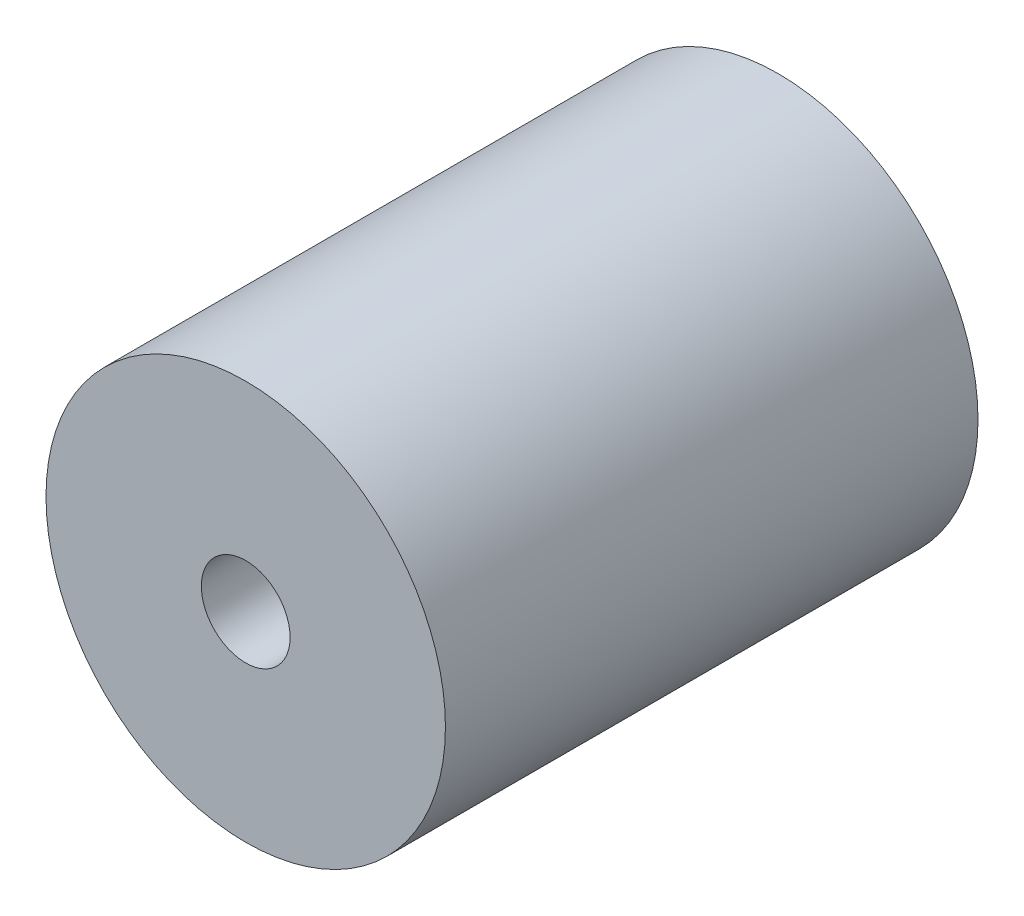
SolidWorks part; units mm, degrees
ref_plane "Plan de face" through (0, 0, 0) normal (0, 0, 1) x (1, 0, 0)
ref_plane "Plan de dessus" through (0, 0, 0) normal (0, 1, 0) x (1, 0, 0)
ref_plane "Plan de droite" through (0, 0, 0) normal (1, 0, 0) x (0, 0, -1)
sketch "Esquisse1" plane through (0, 0, 0) normal (0, 0, 1) x (1, 0, 0)
  circle A0 centre (0, 0) radius 14.2875
  dimension "D1" = 28.575
extrude "Boss.-Extru.1" add sketch "Esquisse1" along normal blind 38.1
sketch "Esquisse2" plane through (0, 0, 38.1) normal (0, 0, 1) x (1, 0, 0)
  circle A0 centre (0, 0) radius 3.175
  dimension "D1" = 6.35
extrude "Enlèv. mat.-Extru.1" cut sketch "Esquisse2" against normal through all
